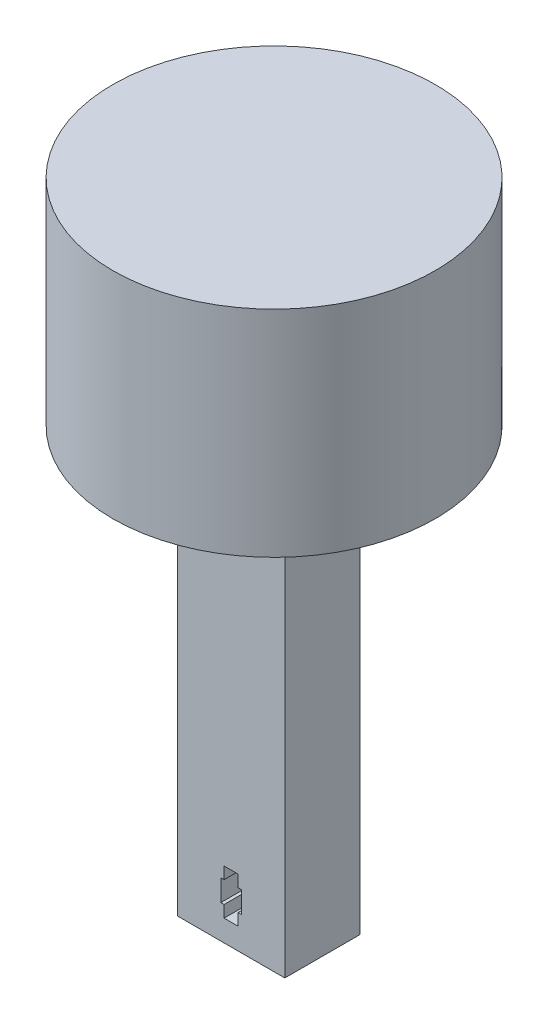
SolidWorks part; units mm, degrees
ref_plane "前视基准面" through (0, 0, 0) normal (0, 0, 1) x (1, 0, 0)
ref_plane "上视基准面" through (0, 0, 0) normal (0, 1, 0) x (1, 0, 0)
ref_plane "右视基准面" through (0, 0, 0) normal (1, 0, 0) x (0, 0, -1)
sketch "草图1" plane through (0, 0, 0) normal (0, 1, 0) x (1, 0, 0)
  circle A0 centre (0, 0) radius 15
  dimension "D1" = 30
extrude "凸台-拉伸1" add sketch "草图1" along normal blind 20
sketch "草图2" plane through (0, 0, 0) normal (0, -1, 0) x (1, 0, 0)
  line L0 (0, 0) -> (0, 20.694) construction
  line L1 (0, 0) -> (12, 0) construction
  circle A0 centre (12, 0) radius 1.5
  circle A1 centre (-12, 0) radius 1.5
  dimension "D1" = 3
  dimension "D2" = 24
extrude "切除-拉伸1" cut sketch "草图2" against normal blind 15
sketch "草图3" plane through (0, 0, 0) normal (0, -1, 0) x (1, 0, 0)
  line L0 (0, 0) -> (0, 0.5) construction
  line L2 (5, -3) -> (-5, -3)
  line L3 (5, -3) -> (5, 4)
  line L4 (5, 4) -> (-5, 4)
  line L5 (-5, -3) -> (-5, 4)
  line L6 (5, -3) -> (-5, 4) construction
  line L7 (5, 4) -> (-5, -3) construction
  dimension "D1" = 10
  dimension "D2" = 7
  dimension "D3" = 0.5
extrude "凸台-拉伸2" add sketch "草图3" along normal blind 40
sketch "草图4" plane through (0, 0, 4) normal (0, 0, 1) x (1, 0, 0)
  line L0 (0, -40) -> (0, -35.9) construction
  line L1 (5, -40) -> (-5, -40) construction
  line L3 (-0.65, -38) -> (0.65, -38)
  line L4 (-0.65, -38) -> (-0.65, -33.8)
  line L5 (-0.65, -33.8) -> (0.65, -33.8)
  line L6 (0.65, -38) -> (0.65, -33.8)
  line L7 (-0.65, -38) -> (0.65, -33.8) construction
  line L8 (-0.65, -33.8) -> (0.65, -38) construction
  dimension "D1" = 2
  dimension "D2" = 4.2
  dimension "D3" = 1.3
extrude "切除-拉伸2" cut sketch "草图4" against normal through all
sketch "草图5" plane through (0, 0, -3) normal (0, 0, 1) x (1, 0, 0)
  line L0 (0, -33.8) -> (0, -38) construction
  line L1 (0.65, -33.8) -> (-0.65, -33.8) construction
  line L2 (-0.65, -38) -> (0.65, -38) construction
  line L3 (0.65, -38) -> (0.65, -33.8) construction
  line L4 (-0.65, -38.5) -> (0.65, -38.5)
  line L5 (-0.65, -38.5) -> (-0.65, -33.3)
  line L6 (-0.65, -33.3) -> (0.65, -33.3)
  line L7 (0.65, -38.5) -> (0.65, -33.3)
  line L8 (-0.65, -38.5) -> (0.65, -33.3) construction
  line L9 (-0.65, -33.3) -> (0.65, -38.5) construction
  point P6 (0, -35.9)
  point P11 (0, 0)
  dimension "D1" = 5.2
extrude "切除-拉伸3" cut sketch "草图5" along normal blind 2
sketch "草图6" plane through (0, 0, 4) normal (0, 0, 1) x (1, 0, 0)
  line L0 (0, -33.3) -> (0, -38.5) construction
  line L1 (0.65, -33.3) -> (-0.65, -33.3) construction
  line L2 (-0.65, -38.5) -> (0.65, -38.5) construction
  line L4 (-0.95, -36.9) -> (0.95, -36.9)
  line L5 (-0.95, -36.9) -> (-0.95, -34.9)
  line L6 (-0.95, -34.9) -> (0.95, -34.9)
  line L7 (0.95, -36.9) -> (0.95, -34.9)
  line L8 (-0.95, -36.9) -> (0.95, -34.9) construction
  line L9 (-0.95, -34.9) -> (0.95, -36.9) construction
  point P6 (0, -35.9)
  dimension "D1" = 2
  dimension "D2" = 1.9
extrude "切除-拉伸4" cut sketch "草图6" against normal through all
